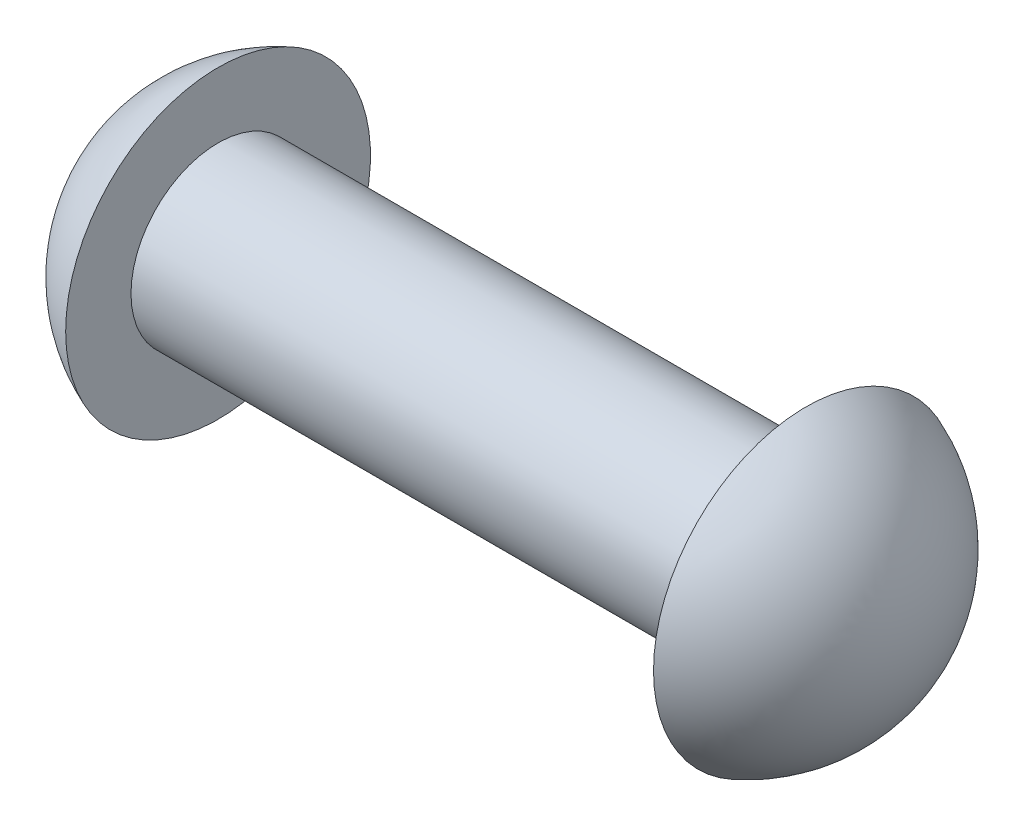
SolidWorks part; units mm, degrees
ref_plane "Plane1" through (0, 0, 0) normal (0, 0, 1) x (1, 0, 0)
ref_plane "Plane2" through (0, 0, 0) normal (0, 1, 0) x (1, 0, 0)
ref_plane "Plane3" through (0, 0, 0) normal (1, 0, 0) x (0, 0, -1)
sketch "Sketch1" plane through (0, 0, 0) normal (0, 0, 1) x (1, 0, 0)
  line L0 (-39, 0) -> (6, 0) construction
  line L1 (-31.8, 0) -> (0, 0)
  line L2 (-27, 4) -> (-27, 7)
  line L3 (-27, 4) -> (0, 4)
  line L4 (0, 4) -> (0, 0)
  arc A0 (-27, 7) -> (-31.8, 0) centre (-24.3, 0.0029) ccw
  point P12 (-27, 4)
  dimension "HeadRadius" = 7.5
  dimension "Diameter" = 8
  dimension "GripLength" = 27
  dimension "HeadHt" = 4.8
  dimension "HeadDia" = 14
revolve "Base-Revolve" add sketch "Sketch1" angle 360 about L0
sketch "Sketch3" plane through (0, 0, 0) normal (0, 0, 1) x (1, 0, 0)
  line L0 (-49, 0) -> (71, 0) construction
  line L1 (0, 0) -> (4.8, 0)
  line L2 (0, 0) -> (0, 7)
  arc A0 (4.8, 0) -> (0, 7) centre (-2.7, 0.0029) ccw
  dimension "D3" = 7.5
  dimension "D1" = 14
  dimension "D2" = 4.8
revolve "HeadTypeA" add sketch "Sketch3" angle 360 about L0
sketch "Sketch4" plane through (0, 0, 0) normal (0, 0, 1) x (1, 0, 0)
  line L0 (30, 0) -> (-54, 0) construction
  line L1 (-39, 0) -> (6, 0) construction
  line L2 (0, 0) -> (0, 7)
  line L3 (0, 7) -> (-3.9097, 4)
  line L4 (-3.9097, 0) -> (0, 0)
  line L5 (0, -7) -> (-3.9097, -4) construction
  line L6 (-3.9097, 0) -> (-3.9097, 4)
  dimension "D1" = 14
  dimension "D3" = 8
  dimension "D2" = 75
revolve "HeadTypeB" [suppressed] add sketch "Sketch4" angle 360 about L0
equation "\"D1@Sketch3\" = \"HeadDia@Sketch1\""
equation "\"D2@Sketch3\" = \"HeadHt@Sketch1\""
equation "\"D3@Sketch3\" = \"HeadRadius@Sketch1\""
equation "\"D1@Sketch4\" = \"HeadDia@Sketch1\""
equation "\"D3@Sketch4\" = \"Diameter@Sketch1\""
